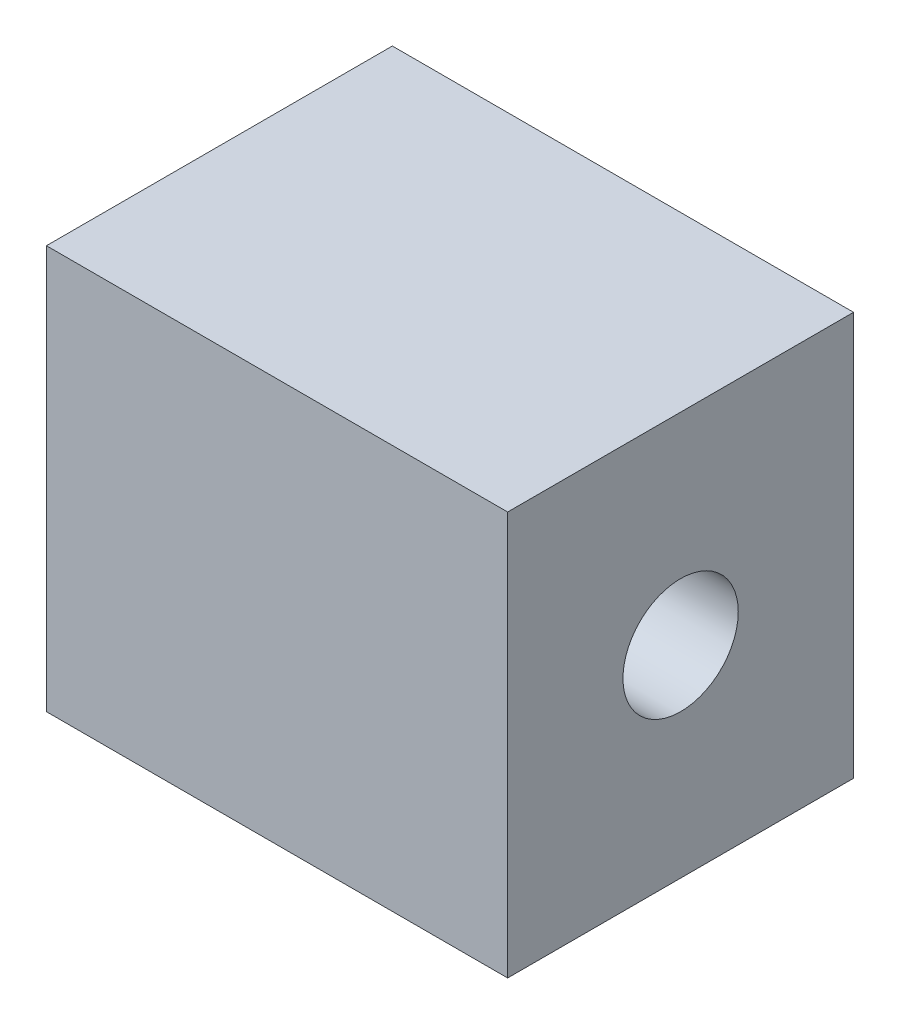
SolidWorks part; units mm, degrees
ref_plane "前视基准面" through (0, 0, 0) normal (0, 0, 1) x (1, 0, 0)
ref_plane "上视基准面" through (0, 0, 0) normal (0, 1, 0) x (1, 0, 0)
ref_plane "右视基准面" through (0, 0, 0) normal (1, 0, 0) x (0, 0, -1)
sketch "草图1" plane through (0, 0, 0) normal (0, 0, 1) x (1, 0, 0)
  line L1 (-20, 17.5) -> (20, 17.5)
  line L2 (-20, 17.5) -> (-20, -17.5)
  line L3 (-20, -17.5) -> (20, -17.5)
  line L4 (20, 17.5) -> (20, -17.5)
  line L5 (-20, 17.5) -> (20, -17.5) construction
  line L6 (-20, -17.5) -> (20, 17.5) construction
  point P0 (0, 0)
  dimension "D1" = 40
  dimension "D2" = 35
extrude "凸台-拉伸1" add sketch "草图1" along normal blind 30
sketch "草图2" plane through (0, 0, 0) normal (0, 0, 1) x (1, 0, 0)
  line L1 (-14, 10.5) -> (14, 10.5) construction
  line L2 (-14, 10.5) -> (-14, -10.5) construction
  line L3 (-14, -10.5) -> (14, -10.5) construction
  line L4 (14, 10.5) -> (14, -10.5) construction
  line L5 (-14, 10.5) -> (14, -10.5) construction
  line L6 (-14, -10.5) -> (14, 10.5) construction
  circle A0 centre (-14, 10.5) radius 2.5
  circle A1 centre (14, 10.5) radius 2.5
  circle A2 centre (14, -10.5) radius 2.5
  circle A3 centre (-14, -10.5) radius 2.5
  point P0 (0, 0)
  dimension "D3" = 5
  dimension "D1" = 28
  dimension "D2" = 21
  dimension "D4" = 2
  dimension "D5" = 2
extrude "切除-拉伸2" cut sketch "草图2" along normal blind 20
sketch "草图3" plane through (20, 0, 0) normal (1, 0, 0) x (0, 0, -1)
  line L0 (-15, 17.5) -> (-15, -17.5) construction
  line L1 (-30, 17.5) -> (0, 17.5) construction
  line L2 (-30, -17.5) -> (0, -17.5) construction
  circle A0 centre (-15, 0) radius 5
  point P2 (-15, 0)
  dimension "D1" = 10
extrude "切除-拉伸3" cut sketch "草图3" against normal through all
